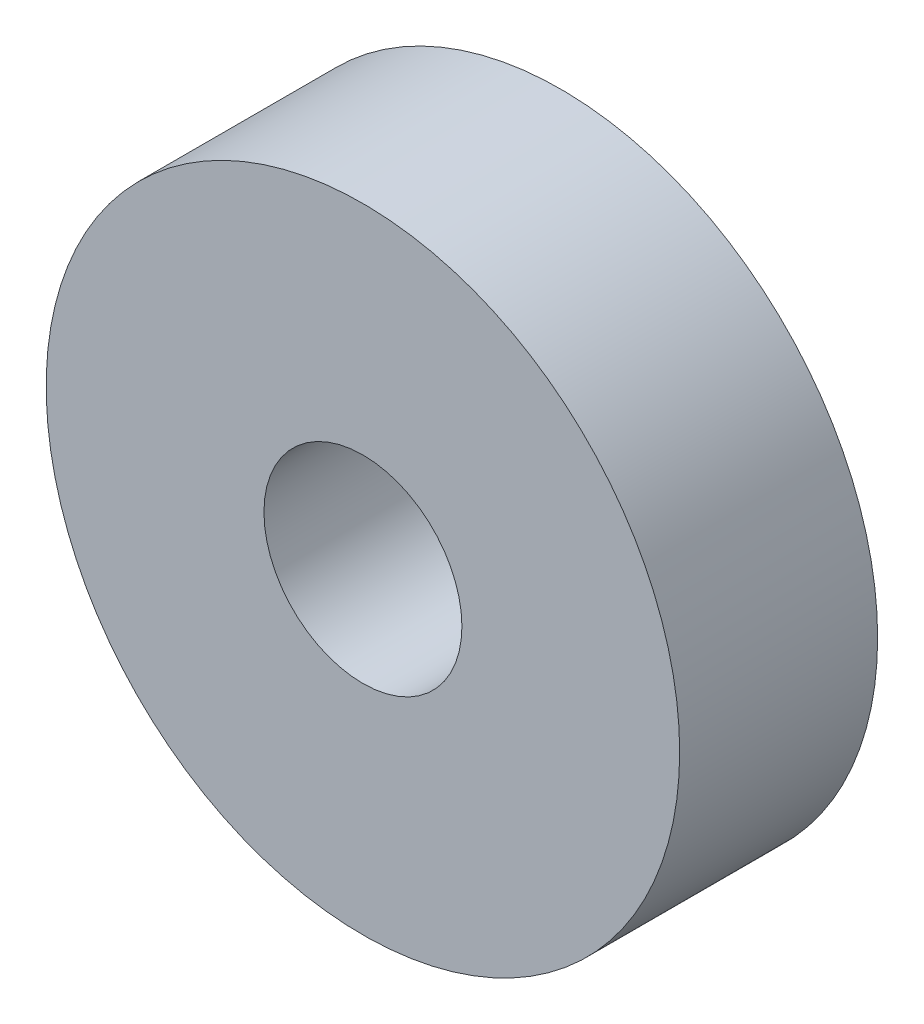
SolidWorks part; units mm, degrees
ref_plane "Front" through (0, 0, 0) normal (0, 0, 1) x (1, 0, 0)
ref_plane "Top" through (0, 0, 0) normal (0, 1, 0) x (1, 0, 0)
ref_plane "Right" through (0, 0, 0) normal (1, 0, 0) x (0, 0, -1)
sketch "Эскиз1" plane through (0, 0, 0) normal (0, 0, 1) x (1, 0, 0)
  circle A0 centre (0, 0) radius 2.5
  circle A1 centre (0, 0) radius 8
  dimension "D1" = 16
  dimension "D2" = 5
extrude "Бобышка-Вытянуть1" add sketch "Эскиз1" along normal mid plane 5
